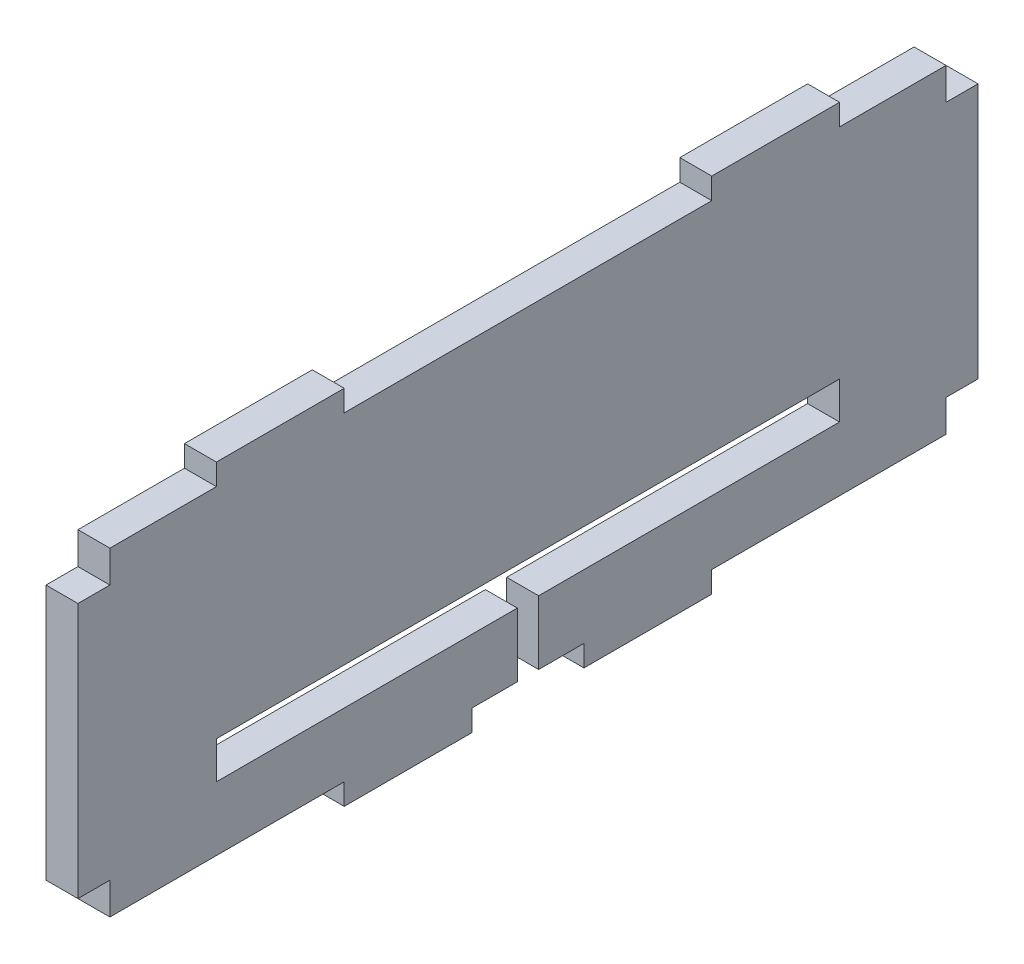
SolidWorks part; units mm, degrees
ref_plane "Front Plane" through (0, 0, 0) normal (0, 0, 1) x (1, 0, 0)
ref_plane "Top Plane" through (0, 0, 0) normal (0, 1, 0) x (1, 0, 0)
ref_plane "Right Plane" through (0, 0, 0) normal (1, 0, 0) x (0, 0, -1)
sketch "Sketch1" plane through (0, 0, 0) normal (1, 0, 0) x (0, 0, -1)
  line L0 (0, 0) -> (0, -32841.5669)
  line L1 (0, 0) -> (32841.5669, 0)
  line L2 (0, 5) -> (3, 5)
  line L3 (0, 0) -> (84.51, 0)
  line L4 (0, 0) -> (0, 34)
  line L5 (0, 34) -> (84.51, 34)
  line L6 (84.51, 0) -> (84.51, 34)
  line L11 (3, 5) -> (3, 2)
  line L12 (3, 2) -> (25, 2)
  line L13 (25, 2) -> (25, 0)
  line L14 (25, 0) -> (37, 0)
  line L15 (37, 0) -> (37, 2)
  line L16 (13, 8) -> (41.255, 8)
  line L17 (41.255, 8) -> (41.255, 2)
  line L18 (41.255, 2) -> (37, 2)
  line L19 (13, 8) -> (13, 11.5)
  line L20 (13, 11.5) -> (71.51, 11.5)
  line L21 (71.51, 11.5) -> (71.51, 8)
  line L22 (71.51, 8) -> (43.255, 8)
  line L23 (43.255, 8) -> (43.255, 2)
  line L24 (43.255, 2) -> (47.51, 2)
  line L25 (47.51, 2) -> (47.51, 0)
  line L26 (47.51, 0) -> (59.51, 0)
  line L27 (59.51, 0) -> (59.51, 2)
  line L28 (59.51, 2) -> (81.51, 2)
  line L29 (81.51, 2) -> (81.51, 5)
  line L30 (81.51, 5) -> (84.51, 5)
  line L31 (0, 29) -> (3, 29)
  line L32 (3, 29) -> (3, 32)
  line L33 (3, 32) -> (13, 32)
  line L34 (13, 32) -> (13, 34)
  line L35 (13, 34) -> (25, 34)
  line L36 (25, 34) -> (25, 32)
  line L37 (25, 32) -> (59.51, 32)
  line L38 (59.51, 32) -> (59.51, 34)
  line L39 (59.51, 34) -> (71.51, 34)
  line L40 (71.51, 34) -> (71.51, 32)
  line L41 (71.51, 32) -> (81.51, 32)
  line L42 (81.51, 32) -> (81.51, 29)
  line L43 (81.51, 29) -> (84.51, 29)
  dimension "D2" = 84.51
  dimension "D3" = 2
  dimension "D4" = 3
  dimension "D5" = 3
  dimension "D6" = 10.51
  dimension "D7" = 12
  dimension "D8" = 22
  dimension "D9" = 3
  dimension "D10" = 3
  dimension "D11" = 12
  dimension "D12" = 22
  dimension "D13" = 12
  dimension "D14" = 24
  dimension "D15" = 2
  dimension "D16" = 12
  dimension "D17" = 2
  dimension "D18" = 3
  dimension "D19" = 5
  dimension "D20" = 3
  dimension "D21" = 12
  dimension "D22" = 12
  dimension "D23" = 3.5
  dimension "D24" = 6
  dimension "D25" = 2
  dimension "D26" = 34
  dimension "D27" = 13
  dimension "D28" = 13
  dimension "D29" = 34.51
  dimension "D31" = 3
extrude "Boss-Extrude1" add sketch "Sketch1" along normal blind 3 contours L43 L42 L41 L40 L5 L38 L37 L36 L34 L33 L32 L31 L4 L2 L11 L12 L13 L3 L15 L18 L17 L16 L19 L20 L21 L22 L23 L24 L25 L27 L28 L29 L30 L6
